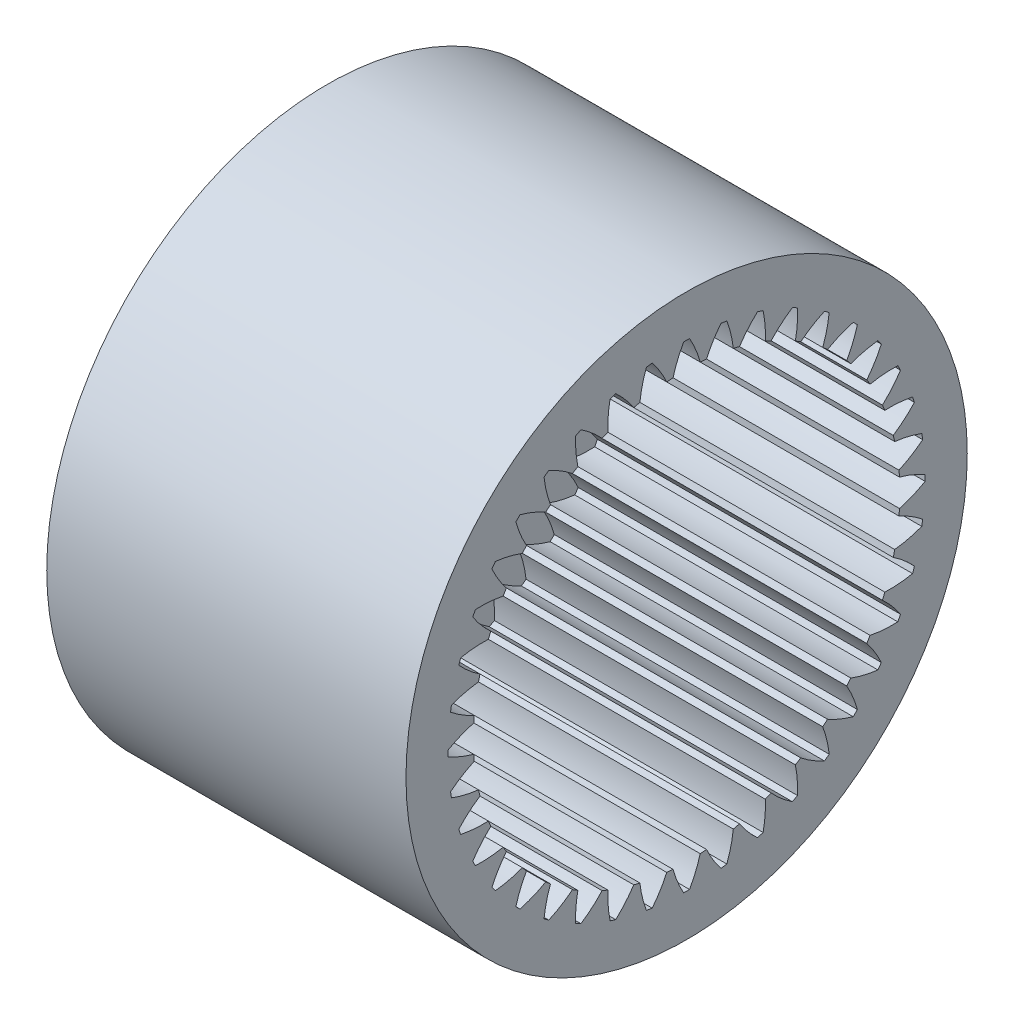
SolidWorks part; units mm, degrees
ref_plane "Plane1" through (0, 0, 0) normal (0, 0, 1) x (1, 0, 0)
ref_plane "Plane2" through (0, 0, 0) normal (0, 1, 0) x (1, 0, 0)
ref_plane "Plane3" through (0, 0, 0) normal (1, 0, 0) x (0, 0, -1)
other "Configuration Table"
sketch "HoldingSke" plane through (0, 0, 0) normal (0, 1, 0) x (1, 0, 0)
  line L0 (0, 0) -> (0.383, -0.3214)
  line L1 (-15, 0) -> (100, 0) construction
  line L2 (0, 0) -> (-2.1039, 2.3779)
  line L3 (0, 0) -> (-11.863, 4.5341)
  line L4 (0, 0) -> (6.6156, 5.5511)
  line L5 (0, 0) -> (-23.7986, -8.8762)
  line L6 (0, 0) -> (-10.5278, -7.1032)
  line L7 (-2.1039, 2.3779) -> (3.3635, 27.1825)
  line L8 (-76.2, 4.3779) -> (-54.61, 4.3779)
  line L9 (-71.009, 38.7566) -> (-53.1078, 45.2721)
  line L10 (-76.2, 71.12) -> (104.1128, 71.12)
  line L11 (0, 0) -> (-54, 0)
  line L12 (-76.2, 101.6) -> (-76.133, 101.6)
  line L13 (24.9733, 27.94) -> (52.9518, 28.4284)
  line L14 (24.9733, 27.94) -> (24.9743, 27.94)
  line L15 (24.9733, 27.94) -> (100.4006, 29.5858)
  circle A0 centre (0, 0) radius 50
  circle A1 centre (0, 0) radius 12.7
  circle A2 centre (0, 0) radius 12.7
  dimension "MHD" = 25.4
  dimension "Hub_dia" = 25.4
  dimension "Diameter" = 100
  dimension "Num_teeth" = 40
  dimension "Pitch" = 0.5
  dimension "Overall_len" = 25.4
  dimension "Show_teeth" = 40
  dimension "Thickness" = 12.7
  dimension "OAL" = 25.4001
  dimension "T_dim" = 21.59
  dimension "Ap" = 20
  dimension "H" = 19.05
  dimension "Pitch_radius" = 180.3128
  dimension "Width" = 54
  dimension "Backlash" = 0.067
  dimension "Addendum_fac" = 1
  dimension "Dedendum_fac" = 1.25
  dimension "Clearance_fac" = 0.25
  dimension "Dedendum_add" = 0.001
  dimension "Module" = 2
sketch "BasProSke" plane through (0, 0, 0) normal (0, 1, 0) x (1, 0, 0)
  line L0 (-10, 0) -> (60, 0) construction
  line L1 (0, 38) -> (0, 50)
  line L2 (0, 38) -> (54, 38)
  line L3 (54, 38) -> (54, 50)
  line L4 (54, 50) -> (0, 50)
  dimension "Diameter" = 100
  dimension "Thickness" = 54
  dimension "Inside_diameter" = 76
revolve "Base-Revolve" add sketch "BasProSke" angle 360 about L0
sketch "TooCutSke" plane through (0, 0, 0) normal (1, 0, 0) x (0, 0, -1)
  line L3 (1.7379, 39.9622) -> (1.7379, 53.6633) construction
  line L4 (0, 0) -> (0, 59.563) construction
  line L5 (0, 0) -> (-5.3609, 68.1169) construction
  line L6 (-16.8604, 32.6066) -> (35.072, 36.6938) construction
  circle A0 centre (0, 0) radius 40 construction
  circle A1 centre (0, 0) radius 42.501 construction
  circle A2 centre (0, 0) radius 33.8289 construction
  circle A3 centre (0, 0) radius 37.9746 construction
  arc A4 (2.4273, 37.8969) -> (0.5225, 42.4978) centre (-16.8604, 32.6066) ccw
  arc A5 (2.4273, 37.8969) -> (-2.4273, 37.8969) centre (0, 0) ccw
  arc A6 (0.5225, 42.4978) -> (-0.5225, 42.4978) centre (0, 0) ccw
  arc A7 (-0.5225, 42.4978) -> (-2.4273, 37.8969) centre (16.8604, 32.6066) ccw
  dimension "Pitch_dia" = 80
  dimension "Base_dia" = 67.6579
  dimension "Root_dia" = 85.002
  dimension "Overcut_dia" = 75.9492
  dimension "Flank_rad" = 20
  dimension "Half_ang" = 4.5
  dimension "Half_CT" = 1.7379
extrude "ToothCut" cut sketch "TooCutSke" along normal through all
fillet "Breaks" [suppressed] radius 0.2
fillet "RootFillets" [suppressed] radius 0.501
pattern_circular "TeethCuts" count 40 every 9 about axis through (-10, 0, 0) along (1, 0, 0) of "RootFillets", "Breaks", "ToothCut"
sketch "Sketch2" plane through (0, 0, 0) normal (-1, 0, 0) x (0, 0, 1)
  circle A0 centre (0, 0) radius 11
  circle A1 centre (0, 0) radius 50
  circle A2 centre (0, 0) radius 50
  dimension "D2" = 22
  dimension "D1" = 0
extrude "Boss-Extrude1" add sketch "Sketch2" along normal blind 10
equation "' \"Module@HoldingSke\" = 6.35"
equation "' \"Num_teeth@HoldingSke\" = 24"
equation "' \"Ap@HoldingSke\" =  14.5"
equation "' \"Ap@HoldingSke\" = 14.5"
equation "' \"Width@HoldingSke\" = 12"
equation "' \"Diameter@HoldingSke\" = 8 * 25.4"
equation "' \"Show_teeth@HoldingSke\" = 100"
equation "' \"Backlash@HoldingSke\" = 0.009 * 25.4"
equation "' \"Addendum_fac@HoldingSke\" = 1.0"
equation "' \"Dedendum_fac@HoldingSke\" = 1.25"
equation "' \"Dedendum_add@HoldingSke\" = 0.00005 * 25.4"
equation "' \"Clearance_fac@HoldingSke\" = 0.25"
equation "\"Pitch@HoldingSke\" = 1 / \"Module@HoldingSke\" "
equation "\"Overcut_dia@TooCutSke\" = (\"Num_teeth@HoldingSke\" - 2 * \"Addendum_fac@HoldingSke\") / \"Pitch@HoldingSke\" - 0.002 * 25.4"
equation "\"Pitch_dia@TooCutSke\" = \"Num_teeth@HoldingSke\" / \"Pitch@HoldingSke\""
equation "\"Base_dia@TooCutSke\" = \"Num_teeth@HoldingSke\" / \"Pitch@HoldingSke\" * cos((\"Ap@HoldingSke\"  * 3.14159265 / 180)) * 0.90"
equation "\"Root_dia@TooCutSke\" = \"Num_teeth@HoldingSke\"  / \"Pitch@HoldingSke\" + 2 *  \"Dedendum_fac@HoldingSke\"/ \"Pitch@HoldingSke\" + \"Dedendum_add@HoldingSke\" * 2"
equation "\"Half_ang@TooCutSke\" = 180 / \"Num_teeth@HoldingSke\""
equation "\"Half_CT@TooCutSke\" = \"Num_teeth@HoldingSke\" / \"Pitch@HoldingSke\" * sin((3.14159265 / 2 / \"Num_teeth@HoldingSke\")) / 2 + 10 * \"Backlash@HoldingSke\" / 4"
equation "\"Flank_rad@TooCutSke\" = \"Num_teeth@HoldingSke\" / \"Pitch@HoldingSke\" / 4"
equation "\"Radius@RootFillets\"= \"Clearance_fac@HoldingSke\" / \"Pitch@HoldingSke\" + \"Dedendum_add@HoldingSke\""
equation "\"Break_rad@Breaks\" = 0.02 / \"Pitch@HoldingSke\" * 5"
equation "\"Num_teeth@TeethCuts\" = int( \"Show_teeth@HoldingSke\" ) + 1"
equation "\"Num_teeth@TeethCuts\" = ((sgn( \"Num_teeth@TeethCuts\" - \"Num_teeth@HoldingSke\" )-1)*( \"Num_teeth@TeethCuts\" - \"Num_teeth@HoldingSke\" ))/-2+ \"Num_teeth@HoldingSke\""
equation "\"Num_teeth@TeethCuts\" = ((sgn( \"Num_teeth@TeethCuts\" - 2.0)+1)*( \"Num_teeth@TeethCuts\" - 2.0))/2 +2.0"
equation "\"Angle@TeethCuts\" = 360.0 / \"Num_teeth@HoldingSke\""
equation "\"Diameter@BasProSke\" = \"Num_teeth@HoldingSke\"  / \"Pitch@HoldingSke\" + 2 *  \"Dedendum_fac@HoldingSke\"/ \"Pitch@HoldingSke\" + \"Dedendum_add@HoldingSke\" * 2 + 0.002 * 25.4"
equation "\"Diameter@BasProSke\" = ((sgn( \"Diameter@BasProSke\"  - \"Diameter@HoldingSke\" )+1)*( \"Diameter@BasProSke\"  - \"Diameter@HoldingSke\" ))/2 + \"Diameter@HoldingSke\""
equation "\"Inside_diameter@BasProSke\" =  (\"Num_teeth@HoldingSke\" - 2 * \"Addendum_fac@HoldingSke\") / \"Pitch@HoldingSke\" "
equation "\"Thickness@BasProSke\"  = \"Width@HoldingSke\""
